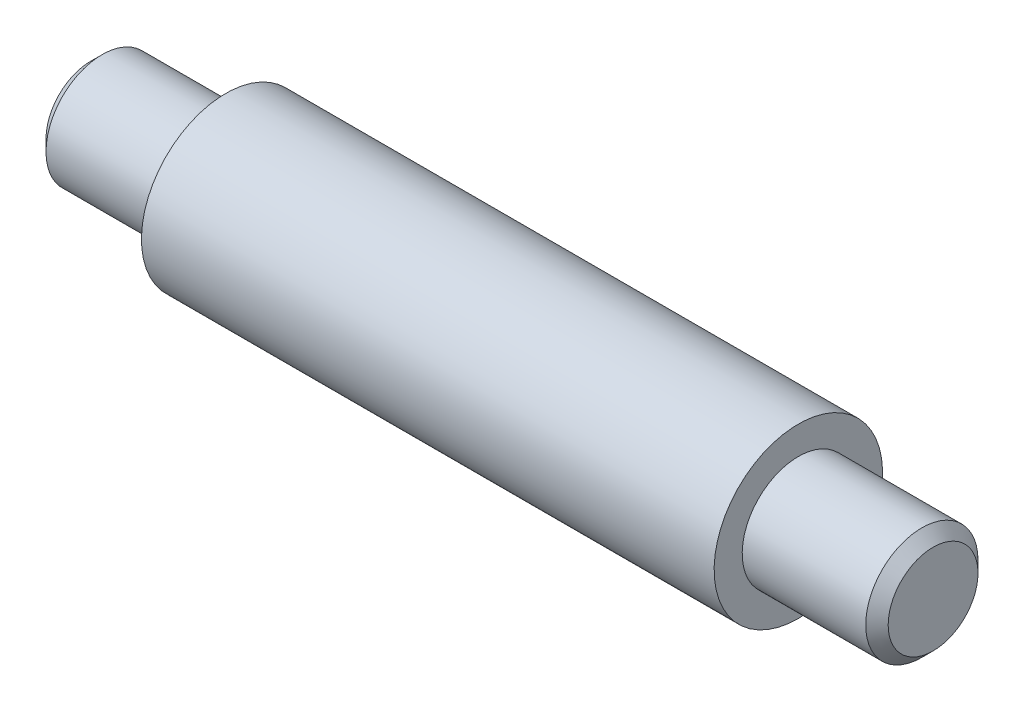
SolidWorks part; units mm, degrees
ref_plane "Front Plane" through (0, 0, 0) normal (0, 0, 1) x (1, 0, 0)
ref_plane "Top Plane" through (0, 0, 0) normal (0, 1, 0) x (1, 0, 0)
ref_plane "Right Plane" through (0, 0, 0) normal (1, 0, 0) x (0, 0, -1)
sketch "Sketch1" plane through (0, 0, 0) normal (0, 0, 1) x (1, 0, 0)
  line L0 (-84.3571, 0) -> (-60.3571, 0)
  line L1 (-60.3571, 0) -> (-60.3571, -5)
  line L2 (-60.3571, -5) -> (41.6429, -5)
  line L3 (41.6429, -5) -> (41.6429, 0)
  line L4 (41.6429, 0) -> (65.6429, 0)
  line L5 (65.6429, 0) -> (65.6429, 10)
  line L6 (65.6429, 10) -> (-84.3571, 10)
  line L7 (-84.3571, 10) -> (-84.3571, 0)
  dimension "D1" = 102
  dimension "D2" = 24
  dimension "D3" = 10
  dimension "D4" = 15
  dimension "D5" = 10
  dimension "D6" = 150
revolve "Revolve1" add sketch "Sketch1" angle 360 about L6
chamfer "Chamfer1" distance 2 angle 45 2 edges at (65.6429, 0, 0) (-84.3571, 0, 0)
